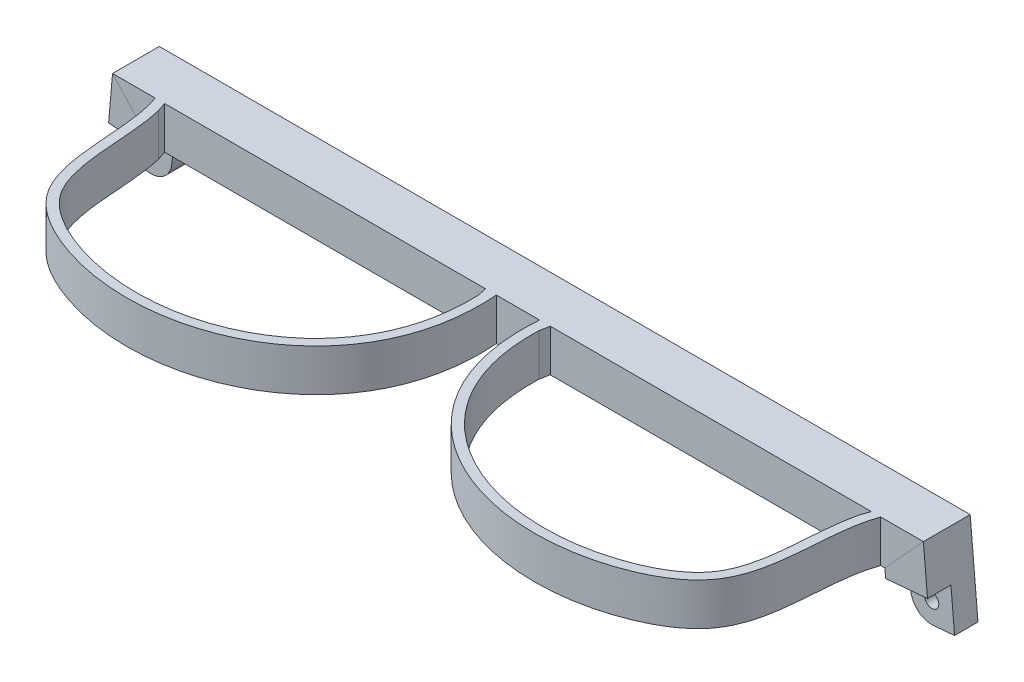
SolidWorks part; units mm, degrees
ref_plane "前视基准面" through (0, 0, 0) normal (0, 0, 1) x (1, 0, 0)
ref_plane "上视基准面" through (0, 0, 0) normal (0, 1, 0) x (1, 0, 0)
ref_plane "右视基准面" through (0, 0, 0) normal (1, 0, 0) x (0, 0, -1)
sketch "草图1" plane through (0, 0, 0) normal (0, 1, 0) x (1, 0, 0)
  line L0 (-85, 29.8187) -> (85, 29.8187)
  line L1 (85, 29.8187) -> (85, -30.1813)
  line L2 (85, -30.1813) -> (-85, -30.1813)
  line L3 (-85, -30.1813) -> (-85, 29.8187)
  line L4 (-77.5, 21.6616) -> (77.5, 21.6616)
  line L5 (-77.5, 21.6616) -> (-77.5, 11.6616)
  line L6 (-77.5, 11.6616) -> (-4.6224, 11.6616)
  line L8 (-74.8263, 9.6616) -> (-6.5113, 9.6616) construction
  line L10 (-4.6224, 11.6616) -> (4.6224, 11.6616)
  line L11 (0, 29.8187) -> (0, -30.1813) construction
  line L12 (77.5, 11.6616) -> (4.6224, 11.6616)
  line L13 (77.5, 21.6616) -> (77.5, 11.6616)
  spline S0 degree 3 poles (-77.5, 11.6616) (-74.4077, 3.1869) (-78.1308, -15.9273) (-40.2589, -37.426) (-2.1163, -20.689) (-4.6224, 11.6616) knots 0 0 0 0 0.246122 0.369792 1 1 1 1
  spline S1 degree 1 poles (-74.8263, 9.6616) (-6.5113, 9.6616) knots 0 0 1 1 construction
  spline S2 degree 3 poles (-74.8263, 9.6616) (-74.5371, 8.4402) (-74.1186, 5.9785) (-73.6218, 0.8691) (-73.2546, -5.557) (-72.241, -11.3706) (-70.6014, -15.2078) (-68.2701, -18.4305) (-63.7315, -21.7629) (-56.8543, -24.5334) (-49.7226, -26.1197) (-40.0582, -26.6566) (-30.6361, -24.878) (-22.3142, -20.9083) (-16.8289, -16.8747) (-12.2912, -11.8166) (-9.4499, -6.76) (-7.8343, -2.2025) (-6.9771, 1.4731) (-6.5812, 4.7599) (-6.4697, 7.5102) (-6.4856, 8.9503) (-6.5113, 9.6616) knots 0.022831 0.022831 0.022831 0.022831 0.052972 0.083113 0.143395 0.203676 0.233817 0.263958 0.324239 0.384521 0.444802 0.505084 0.625647 0.685929 0.74621 0.806492 0.866773 0.896914 0.927055 0.957196 0.972266 0.987337 0.987337 0.987337 0.987337
  spline S3 degree 1 poles (-74.8263, 9.6616) (-75.4985, 11.6616) knots 0 0 1 1
  spline S4 degree 1 poles (-6.5113, 9.6616) (-6.9074, 11.6616) knots 0 0 1 1
  spline S5 degree 1 poles (74.8263, 9.6616) (75.4985, 11.6616) knots 0 0 1 1
  spline S6 degree 1 poles (6.5113, 9.6616) (6.9074, 11.6616) knots 0 0 1 1
  spline S7 degree 3 poles (74.8263, 9.6616) (74.5371, 8.4402) (74.1186, 5.9785) (73.6218, 0.8691) (73.2546, -5.557) (72.241, -11.3706) (70.6014, -15.2078) (68.2701, -18.4305) (63.7315, -21.7629) (56.8543, -24.5334) (49.7226, -26.1197) (40.0582, -26.6566) (30.6361, -24.878) (22.3142, -20.9083) (16.8289, -16.8747) (12.2912, -11.8166) (9.4499, -6.76) (7.8343, -2.2025) (6.9771, 1.4731) (6.5812, 4.7599) (6.4697, 7.5102) (6.4856, 8.9503) (6.5113, 9.6616) knots 0.022831 0.022831 0.022831 0.022831 0.052972 0.083113 0.143395 0.203676 0.233817 0.263958 0.324239 0.384521 0.444802 0.505084 0.625647 0.685929 0.74621 0.806492 0.866773 0.896914 0.927055 0.957196 0.972266 0.987337 0.987337 0.987337 0.987337
  spline S8 degree 3 poles (77.5, 11.6616) (74.4077, 3.1869) (78.1308, -15.9273) (40.2589, -37.426) (2.1163, -20.689) (4.6224, 11.6616) knots 0 0 0 0 0.246122 0.369792 1 1 1 1
  point P3 (0, 29.8187)
  point P25 (0, 11.6616)
  point P31 (0, 21.6616)
  dimension "D1" = 60
  dimension "D2" = 170
  dimension "D3" = 10
  dimension "D4" = 77.5
  dimension "D5" = 2
extrude "frame_前端" add sketch "草图1" along normal blind 9 contours L13 L4 L5 L6 L10 L12 | S8 L12 S5 S7 S6 | S4 S2 S3 L6 S0
sketch "左镜腿扫描截面草图" plane through (77.5, 0, 0) normal (1, 0, 0) x (0, 0, -1)
  line L0 (11.6616, 9) -> (11.6616, 0)
  line L1 (11.6616, 9) -> (11.6616, 0) construction
  line L2 (11.6616, 0) -> (21.6616, 0)
  line L3 (21.6616, 0) -> (21.6616, 9)
  line L4 (21.6616, 9) -> (11.6616, 9)
  line L5 (11.6616, 9) -> (21.6616, 0) construction
  line L6 (11.6616, 0) -> (21.6616, 9) construction
  point P7 (16.6616, 4.5)
ref_plane "左侧镜腿轨迹基准面" through (0, 0, -16.6616) normal (0, 0, -1) x (-1, 0, 0)
sketch "左侧镜腿轨迹草图" plane through (0, 0, -16.6616) normal (0, 0, -1) x (-1, 0, 0)
  line L0 (-77.5, 4.5) -> (-82.5, 4.5)
  line L1 (-77.5, 0) -> (-77.5, 9) construction
  line L2 (-82.5, 4.5) -> (-83.8073, -10.4429)
  dimension "D1" = 5
  dimension "D2" = 15
  dimension "D3" = 95
sweep "左侧connection生成" add profiles "左镜腿扫描截面草图" path "左侧镜腿轨迹草图"
sketch "草图20" plane through (0, 0, -21.6616) normal (0, 0, -1) x (-1, 0, 0)
  line L8 (-79.3245, -10.8351) -> (-83.8073, -10.4429)
  line L9 (-79.3245, -10.8351) -> (-88.2902, -10.0507) construction
  line L10 (-78.3765, 0) -> (-79.3245, -10.8351) construction
  line L11 (-78.9323, -6.3522) -> (-79.3245, -10.8351)
  arc A1 (-83.8073, -10.4429) -> (-78.9323, -6.3522) centre (-83.4151, -5.96) ccw
  point P13 (-79.3245, -10.8351)
  dimension "D1" = 4.5
extrude "左侧connection圆角化" cut sketch "草图20" against normal through all
sketch "孔左" plane through (0, 0, -21.6616) normal (0, 0, -1) x (-1, 0, 0)
  line L4 (-78.9323, -6.3522) -> (-78.3765, 0)
  line L5 (-78.3765, 0) -> (-86.6235, 9)
  line L6 (-86.6235, 9) -> (-88.2902, -10.0507)
  line L7 (-88.2902, -10.0507) -> (-83.8073, -10.4429)
  line L8 (-78.9323, -6.3522) -> (-78.3765, 0)
  line L9 (-78.3765, 0) -> (-86.6235, 9)
  line L10 (-86.6235, 9) -> (-88.2902, -10.0507)
  line L11 (-88.2902, -10.0507) -> (-83.8073, -10.4429)
  arc A1 (-83.8073, -10.4429) -> (-78.9323, -6.3522) centre (-83.4151, -5.96) ccw
  circle A3 centre (-83.4151, -5.96) radius 1.5
  arc A4 (-83.8073, -10.4429) -> (-78.9323, -6.3522) centre (-83.4151, -5.96) ccw
  dimension "D2" = 3
  dimension "D1" = 0
ref_plane "右侧镜腿轨迹基准面" through (0, 0, -16.6616) normal (0, 0, -1) x (-1, 0, 0)
sketch "草图22" plane through (0, 0, -16.6616) normal (0, 0, -1) x (-1, 0, 0)
  line L0 (77.5, 4.5) -> (82.5, 4.5)
  line L1 (77.5, 9) -> (77.5, 0) construction
  line L2 (82.5, 4.5) -> (83.8073, -10.4429)
  dimension "D1" = 5
  dimension "D2" = 15
  dimension "D3" = 95
sketch "草图23" plane through (-77.5, 0, 0) normal (-1, 0, 0) x (0, 0, 1)
  line L2 (-21.6616, 0) -> (-11.6616, 0)
  line L3 (-11.6616, 0) -> (-11.6616, 9)
  line L6 (-21.6616, 9) -> (-21.6616, 0)
  line L7 (-21.6616, 0) -> (-21.6616, 9) construction
  line L8 (-21.6616, 9) -> (-11.6616, 9) construction
  line L9 (-21.6616, 9) -> (-11.6616, 9)
sweep "右侧connection生成" add profiles "草图23" path "草图22"
sketch "草图24" plane through (0, 0, -21.6616) normal (0, 0, -1) x (-1, 0, 0)
  line L2 (88.2902, -10.0507) -> (79.3245, -10.8351) construction
  line L3 (79.3245, -10.8351) -> (83.8073, -10.4429)
  line L4 (79.3245, -10.8351) -> (78.9323, -6.3522)
  line L5 (78.3765, 0) -> (79.3245, -10.8351) construction
  circle A1 centre (83.4151, -5.96) radius 1.5
  arc A2 (78.9323, -6.3522) -> (83.8073, -10.4429) centre (83.4151, -5.96) ccw
  dimension "D3" = 3
  dimension "D1" = 4.5
extrude "右侧孔and_connection圆角化" cut sketch "草图24" against normal through all
ref_plane "线槽口草图基准面" through (0, 0, 0) normal (1, 0, 0) x (0, 0, -1)
sketch "草图26" plane through (0, 0, -21.6616) normal (0, 0, -1) x (-1, 0, 0)
  line L6 (-88.2902, -10.0507) -> (-87.5058, -1.085)
  line L7 (-86.6235, 9) -> (-88.2902, -10.0507) construction
  line L8 (-87.5058, -1.085) -> (-78.5401, -1.8694)
  line L9 (-78.9323, -6.3522) -> (-78.3765, 0) construction
  line L10 (-78.5401, -1.8694) -> (-78.9323, -6.3522)
  line L11 (-88.2902, -10.0507) -> (-83.8073, -10.4429)
  line L12 (-88.2902, -10.0507) -> (-83.8073, -10.4429) construction
  arc A1 (-83.8073, -10.4429) -> (-78.9323, -6.3522) centre (-83.4151, -5.96) ccw
  dimension "D2" = 4.5
  dimension "D1" = 9
  dimension "D3" = 4.5
extrude "挖孔左" cut sketch "孔左" against normal through all contours A3
ref_plane "基准面1" through (0, 0, -16.6616) normal (0, 0, -1) x (-1, 0, 0)
sketch "草图27" plane through (0, 0, -16.6616) normal (0, 0, -1) x (-1, 0, 0)
  line L0 (-87.5058, -1.085) -> (-78.5401, -1.8694)
  line L1 (-78.5401, -1.8694) -> (-78.9323, -6.3522)
  line L2 (-87.5058, -1.085) -> (-88.2902, -10.0507)
  line L3 (-88.2902, -10.0507) -> (-83.8073, -10.4429)
  arc A0 (-83.8073, -10.4429) -> (-78.9323, -6.3522) centre (-83.4151, -5.96) ccw
extrude "左侧connection口" cut sketch "草图27" against normal blind 5
ref_plane "基准面2" through (0, 0, -16.6616) normal (0, 0, -1) x (-1, 0, 0)
sketch "草图30" plane through (0, 0, -16.6616) normal (0, 0, -1) x (-1, 0, 0)
  line L0 (88.2902, -10.0507) -> (83.8073, -10.4429)
  line L1 (88.2902, -10.0507) -> (87.4599, -0.5607)
  line L2 (86.6235, 9) -> (88.2902, -10.0507) construction
  line L3 (87.4599, -0.5607) -> (78.4942, -1.3451)
  line L4 (78.3765, 0) -> (78.9323, -6.3522) construction
  line L5 (78.4942, -1.3451) -> (78.9323, -6.3522)
  arc A0 (78.9323, -6.3522) -> (83.8073, -10.4429) centre (83.4151, -5.96) ccw
extrude "切除-拉伸4" cut sketch "草图30" against normal blind 5
